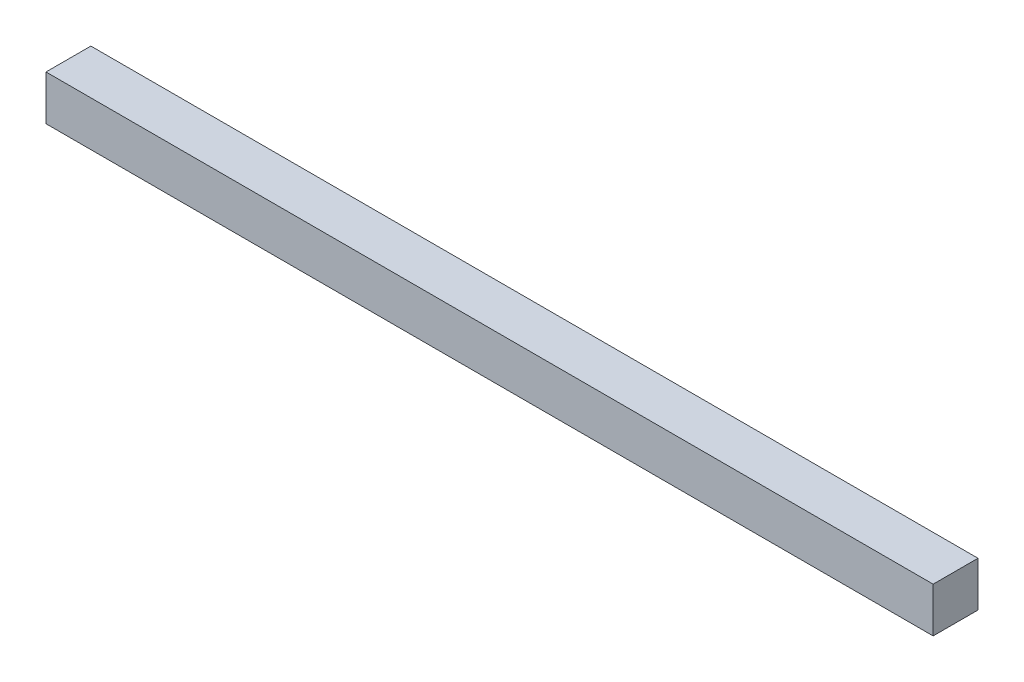
SolidWorks part; units mm, degrees
ref_plane "Front Plane" through (0, 0, 0) normal (0, 0, 1) x (1, 0, 0)
ref_plane "Top Plane" through (0, 0, 0) normal (0, 1, 0) x (1, 0, 0)
ref_plane "Right Plane" through (0, 0, 0) normal (1, 0, 0) x (0, 0, -1)
sketch "Sketch1" plane through (0, 0, 0) normal (0, 0, 1) x (1, 0, 0)
  line L0 (-89, 0) -> (89, 0) construction
  point P3 (0, 0)
  point P4 (0, 0)
  dimension "D1" = 178
sketch "Sketch2" plane through (0, 0, 0) normal (1, 0, 0) x (0, 0, -1)
  line L1 (-4.5, -4.5) -> (4.5, -4.5)
  line L2 (-4.5, -4.5) -> (-4.5, 4.5)
  line L3 (-4.5, 4.5) -> (4.5, 4.5)
  line L4 (4.5, -4.5) -> (4.5, 4.5)
  line L5 (-4.5, -4.5) -> (4.5, 4.5) construction
  line L6 (-4.5, 4.5) -> (4.5, -4.5) construction
  point P0 (0, 0)
  dimension "D1" = 9
extrude "Boss-Extrude1" add sketch "Sketch2" along normal up to vertex (89 mm away) and the other way up to vertex (89 mm away) up to point (89, 0, 0) other way up to point (-89, 0, 0)
